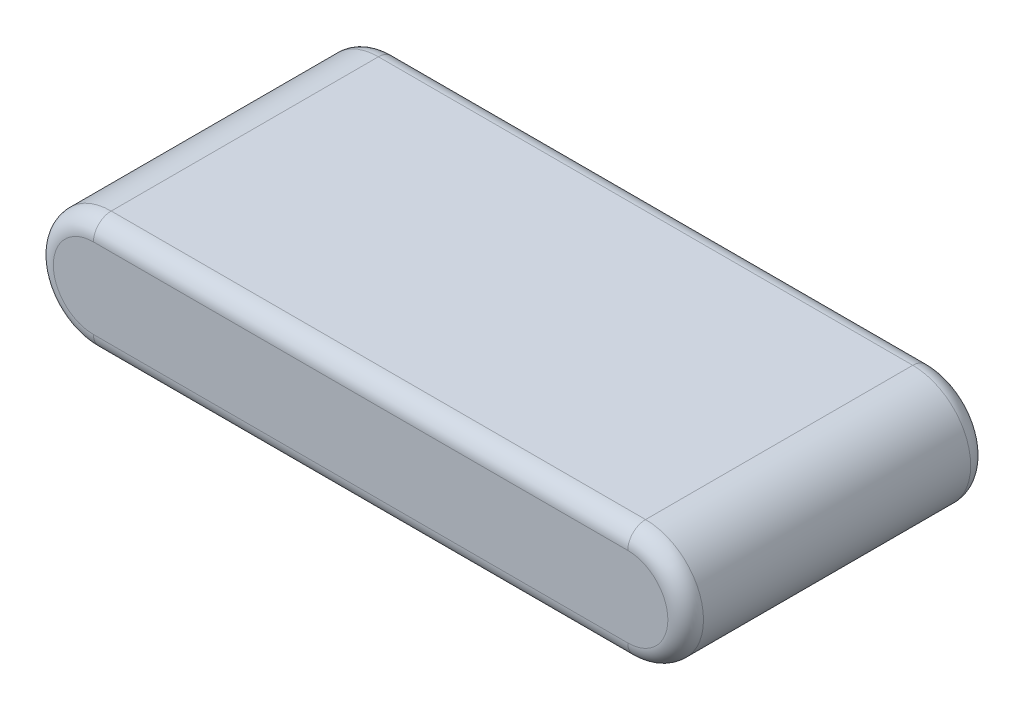
SolidWorks part; units mm, degrees
ref_plane "Plano frontal" through (0, 0, 0) normal (0, 0, 1) x (1, 0, 0)
ref_plane "Plano superior" through (0, 0, 0) normal (0, 1, 0) x (1, 0, 0)
ref_plane "Plano direito" through (0, 0, 0) normal (1, 0, 0) x (0, 0, -1)
sketch "Esboço1" plane through (0, 0, 0) normal (0, 0, 1) x (1, 0, 0)
  line L0 (0, 0) -> (30, 0) construction
  line L3 (0, 3.25) -> (30, 3.25)
  line L4 (0, -3.25) -> (30, -3.25)
  arc A2 (30, -3.25) -> (30, 3.25) centre (30, 0) ccw
  arc A3 (0, 3.25) -> (0, -3.25) centre (0, 0) ccw
  point P3 (15, 0)
  dimension "D1" = 30
extrude "Ressalto-extrusão1" add sketch "Esboço1" along normal blind 17
fillet "Filete1" radius 1 8 edges at (15, -3.25, 0) (33.25, 0, 0) (15, 3.25, 0) (-3.25, 0, 0) (15, 3.25, 17) (33.25, 0, 17) (15, -3.25, 17) (-3.25, 0, 17)
sketch "Esboço2" plane through (0, 0, 17) normal (0, 0, 1) x (1, 0, 0)
  line L0 (-3.25, 0) -> (33.25, 0) construction
  line L2 (0, 3.25) -> (30, 3.25) construction
  line L4 (15, 3.25) -> (15, -3.25) construction
  line L5 (30, -3.25) -> (0, -3.25) construction
  arc A0 (0, 3.25) -> (0, -3.25) centre (0, 0) ccw construction
  arc A1 (30, -3.25) -> (30, 3.25) centre (30, 0) ccw construction
